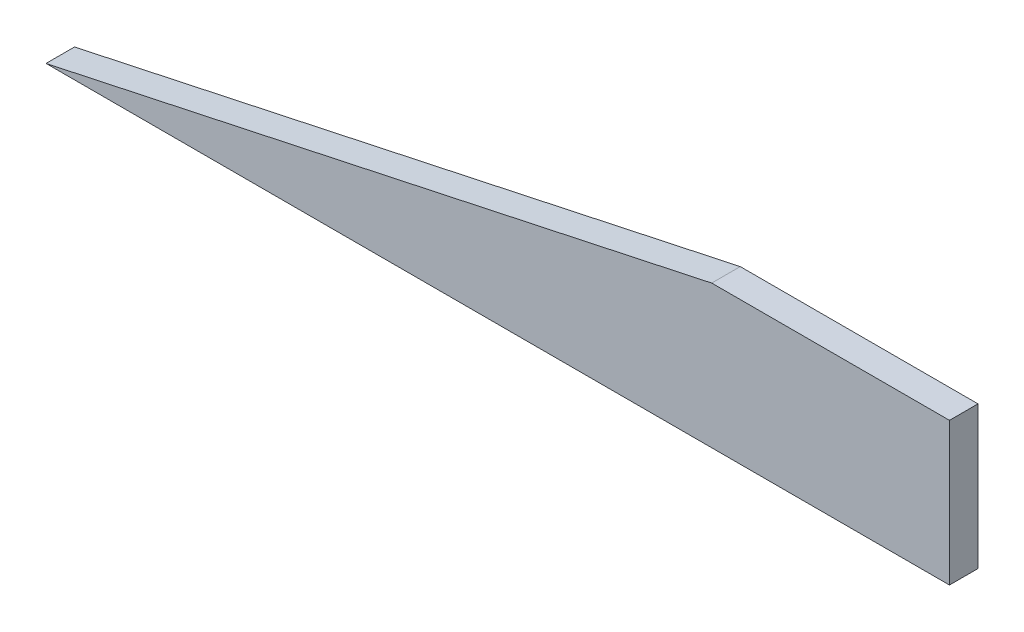
SolidWorks part; units mm, degrees
ref_plane "Front" through (0, 0, 0) normal (0, 0, 1) x (1, 0, 0)
ref_plane "Top" through (0, 0, 0) normal (0, 1, 0) x (1, 0, 0)
ref_plane "Right" through (0, 0, 0) normal (1, 0, 0) x (0, 0, -1)
sketch "Esquisse1" plane through (0, 0, 0) normal (0, 0, 1) x (1, 0, 0)
  line L0 (0, 0) -> (0, 150)
  line L1 (0, 150) -> (-250, 150)
  line L2 (-250, 150) -> (-950, 0)
  line L3 (-950, 0) -> (0, 0)
  dimension "D1" = 150
  dimension "D2" = 250
  dimension "D3" = 950
extrude "Boss.-Extru.1" add sketch "Esquisse1" along normal blind 30
